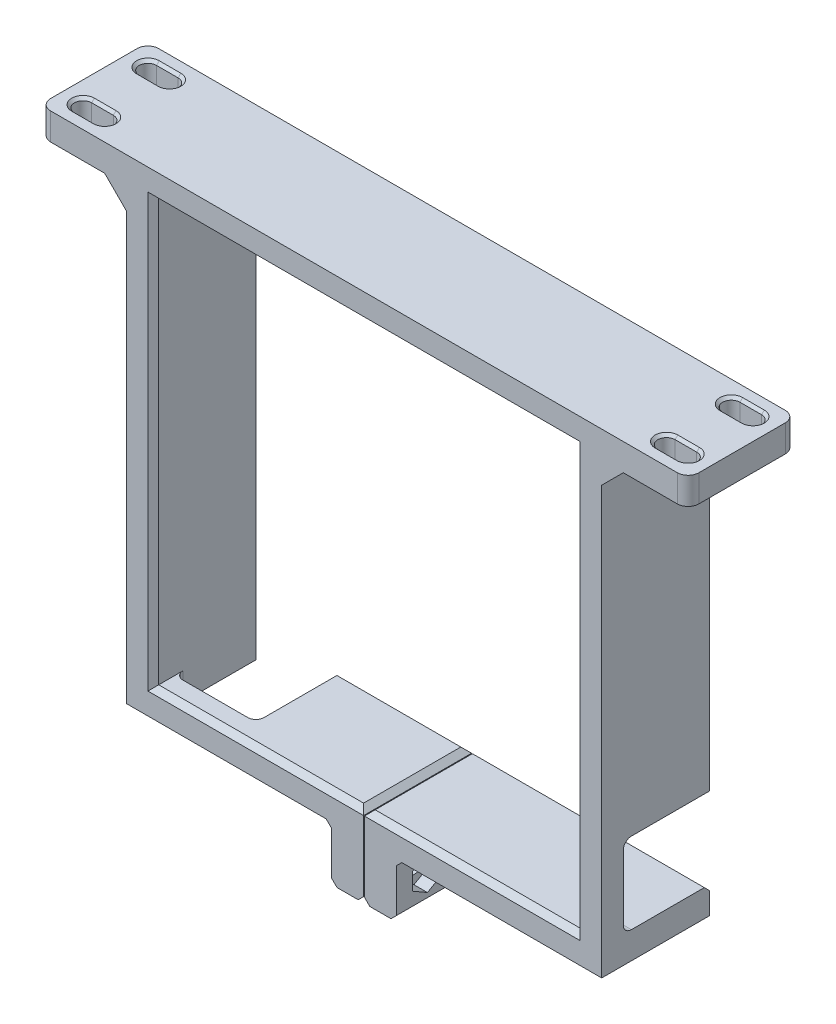
SolidWorks part; units mm, degrees
ref_plane "Front Plane" through (0, 0, 0) normal (0, 0, 1) x (1, 0, 0)
ref_plane "Top Plane" through (0, 0, 0) normal (0, 1, 0) x (1, 0, 0)
ref_plane "Right Plane" through (0, 0, 0) normal (1, 0, 0) x (0, 0, -1)
sketch "Sketch1" plane through (0, 0, 0) normal (0, 0, 1) x (1, 0, 0)
  line L0 (-44.015, -44.015) -> (-44.015, 44.015)
  line L1 (-39.015, -39.015) -> (39.015, -39.015)
  line L2 (-39.015, -39.015) -> (-39.015, 39.015)
  line L3 (-39.015, 39.015) -> (39.015, 39.015)
  line L4 (39.015, -39.015) -> (39.015, 39.015)
  line L5 (-39.015, -39.015) -> (39.015, 39.015) construction
  line L6 (-39.015, 39.015) -> (39.015, -39.015) construction
  line L7 (-44.015, 44.015) -> (44.015, 44.015)
  line L8 (44.015, -44.015) -> (44.015, 44.015)
  line L9 (-44.015, -44.015) -> (44.015, -44.015)
  point P0 (0, 0)
  dimension "D1" = 78.03
  dimension "D2" = 78.03
  dimension "D3" = 5
extrude "Boss-Extrude1" add sketch "Sketch1" along normal blind 20
sketch "Sketch2" plane through (44.015, 0, 0) normal (1, 0, 0) x (0, 0, -1)
  line L0 (-20, -44.015) -> (-20, 44.015) construction
  line L3 (0, -24.015) -> (-16, -24.015)
  line L4 (-16, -39.015) -> (-16, -24.015)
  line L5 (-16, -39.015) -> (0, -39.015)
  line L6 (0, -44.015) -> (0, 44.015) construction
  line L7 (0, -39.015) -> (0, -24.015)
  line L8 (-20, -39.015) -> (0, -39.015) construction
  line L9 (-20, -39.015) -> (0, -39.015) construction
  dimension "D1" = 4
  dimension "D2" = 15
extrude "Cut-Extrude1" cut sketch "Sketch2" against normal blind 20
sketch "Sketch5" plane through (0, 0, 0) normal (0, 0, -1) x (-1, 0, 0)
  line L0 (44.015, -44.015) -> (-44.015, -44.015) construction
  line L1 (-6, -44.015) -> (6, -44.015)
  line L2 (-6, -44.015) -> (-6, -54.015)
  line L3 (-6, -54.015) -> (6, -54.015)
  line L4 (6, -44.015) -> (6, -54.015)
  point P6 (0, -44.015)
  dimension "D1" = 12
  dimension "D2" = 10
extrude "Boss-Extrude2" add sketch "Sketch5" against normal up to surface (20 mm away) up to face at (0, 0, 20)
sketch "Sketch3" plane through (0, 0, 0) normal (0, 0, -1) x (-1, 0, 0)
  line L0 (39.015, -39.015) -> (-44.015, -39.015) construction
  line L1 (-0.075, -39.015) -> (0.075, -39.015)
  line L2 (-0.075, -39.015) -> (-0.075, -54.015)
  line L3 (-0.075, -54.015) -> (0.075, -54.015)
  line L4 (0.075, -39.015) -> (0.075, -54.015)
  line L6 (-6, -54.015) -> (6, -54.015) construction
  point P8 (0, -39.015)
  dimension "D1" = 0.15
extrude "Cut-Extrude2" cut sketch "Sketch3" against normal through all
sketch "Sketch6" plane through (-6, 0, 0) normal (-1, 0, 0) x (0, 0, 1)
  line L0 (0, -54.015) -> (0, -44.015) construction
  line L1 (8.5, -47.4273) -> (5.75, -45.8396)
  line L2 (5.75, -45.8396) -> (3, -47.4273)
  line L3 (3, -47.4273) -> (3, -50.6027)
  line L4 (3, -50.6027) -> (5.75, -52.1904)
  line L5 (5.75, -52.1904) -> (8.5, -50.6027)
  line L6 (8.5, -50.6027) -> (8.5, -47.4273)
  line L8 (17, -47.4273) -> (14.25, -45.8396)
  line L9 (14.25, -45.8396) -> (11.5, -47.4273)
  line L10 (11.5, -47.4273) -> (11.5, -50.6027)
  line L11 (11.5, -50.6027) -> (14.25, -52.1904)
  line L12 (14.25, -52.1904) -> (17, -50.6027)
  line L13 (17, -50.6027) -> (17, -47.4273)
  line L14 (20, -54.015) -> (20, -44.015) construction
  circle A0 centre (5.75, -49.015) radius 2.75 construction
  circle A1 centre (14.25, -49.015) radius 2.75 construction
  point P11 (0, -49.015)
  dimension "D1" = 5.5
  dimension "D2" = 3
  dimension "D3" = 3
extrude "Cut-Extrude3" cut sketch "Sketch6" against normal blind 2.5
sketch "Sketch7" plane through (-6, 0, 0) normal (-1, 0, 0) x (0, 0, 1)
  line L0 (0, -54.015) -> (0, -44.015) construction
  line L1 (20, -54.015) -> (20, -44.015) construction
  circle A0 centre (5.75, -49.015) radius 1.55
  circle A1 centre (14.25, -49.015) radius 1.55
  point P8 (0, -49.015)
  dimension "D3" = 3.1
  dimension "D1" = 5.75
  dimension "D2" = 5.75
extrude "Cut-Extrude4" cut sketch "Sketch7" against normal through all both and the other way through all
sketch "Sketch8" plane through (0, 0, 0) normal (0, 0, -1) x (-1, 0, 0)
  line L0 (-44.015, 39.015) -> (-60.015, 39.015)
  line L1 (-44.015, -24.015) -> (-44.015, 44.015) construction
  line L2 (-60.015, 39.015) -> (-60.015, 44.015)
  line L3 (-60.015, 44.015) -> (-44.015, 44.015)
  line L4 (-39.015, 39.015) -> (39.015, 39.015) construction
  line L5 (-39.015, 39.015) -> (39.015, 39.015) construction
  line L6 (-44.015, 44.015) -> (-44.015, 39.015)
  dimension "D1" = 16
extrude "Boss-Extrude3" add sketch "Sketch8" against normal up to surface (20 mm away) up to face at (0, -23.8825, 20)
sketch "Sketch9" plane through (0, 44.015, 0) normal (0, 1, 0) x (1, 0, 0)
  line L0 (44.015, -20) -> (44.015, 0) construction
  line L1 (44.015, -20) -> (44.015, 0) construction
  line L2 (60.015, -20) -> (60.015, 0) construction
  line L7 (52.015, -16) -> (56.015, -16) construction
  line L8 (52.015, -14.4) -> (56.015, -14.4)
  line L9 (52.015, -17.6) -> (56.015, -17.6)
  line L10 (52.015, -4) -> (56.015, -4) construction
  line L11 (52.015, -2.4) -> (56.015, -2.4)
  line L12 (52.015, -5.6) -> (56.015, -5.6)
  line L13 (44.015, -20) -> (60.015, -20) construction
  line L15 (60.015, 0) -> (-44.015, 0) construction
  arc A0 (52.015, -14.4) -> (52.015, -17.6) centre (52.015, -16) ccw
  arc A1 (56.015, -17.6) -> (56.015, -14.4) centre (56.015, -16) ccw
  arc A2 (52.015, -2.4) -> (52.015, -5.6) centre (52.015, -4) ccw
  arc A3 (56.015, -5.6) -> (56.015, -2.4) centre (56.015, -4) ccw
  point P12 (54.015, -16)
  point P17 (54.015, -4)
  dimension "D2" = 1.6
  dimension "D3" = 4
  dimension "D4" = 4
  dimension "D5" = 4
  dimension "D6" = 4
extrude "Cut-Extrude5" cut sketch "Sketch9" against normal through all
fillet "Fillet8" radius 2 2 edges at (60.015, 41.515, 0) (60.015, 41.515, 20)
fillet "Fillet2" [suppressed] radius 1
mirror "Mirror9" about plane through (0, 0, 0) normal (1, 0, 0) of "Fillet8", "Cut-Extrude5", "Boss-Extrude3", "Cut-Extrude4", "Cut-Extrude3"
chamfer "Chamfer1" distance 4 angle 45 2 edges at (44.015, 39.015, 10) (-44.015, 39.015, 10)
sketch "Sketch10" plane through (0, -44.015, 0) normal (0, -1, 0) x (1, 0, 0)
  line L0 (-39.015, 20) -> (-39.015, 0) construction
  line L1 (-39.015, 20) -> (-39.015, 0) construction
  line L2 (-44.015, 20) -> (-6, 20) construction
  line L3 (-39.015, 0) -> (-24.015, 0)
  line L4 (-39.015, 0) -> (-39.015, 16)
  line L5 (-39.015, 16) -> (-24.015, 16)
  line L6 (-24.015, 0) -> (-24.015, 16)
  dimension "D1" = 4
  dimension "D2" = 15
extrude "Cut-Extrude6" cut sketch "Sketch10" against normal blind 15
fillet "Fillet7" radius 1.5 3 edges at (-39.015, -41.515, 16) (-24.015, -41.515, 16) (41.515, -24.015, 16)
chamfer "Chamfer2" distance 1 angle 45 18 edges at (0, 39.015, 0) (-39.015, -2.5, 0) (39.015, 0, 20) (0, 39.015, 20) (-39.015, 0, 20) (-19.545, -39.015, 20) (39.015, 7.5, 0) (-12.045, -39.015, 0) (-6, -54.015, 10) (-6, -44.015, 10) (6, -44.015, 10) (6, -54.015, 10) (22.045, -39.015, 0) (19.545, -39.015, 20) (0.075, -54.015, 10) (0.075, -39.015, 10) (-0.075, -39.015, 10) (-0.075, -54.015, 10)
chamfer "Chamfer3" distance 0.5 angle 45 32 edges at (-54.015, 39.015, 14.4) (-54.015, 44.015, 14.4) (-50.415, 39.015, 16) (-50.415, 44.015, 16) (-57.615, 39.015, 16) (-57.615, 44.015, 16) (-54.015, 39.015, 17.6) (-54.015, 44.015, 17.6) (-57.615, 39.015, 4) (-54.015, 39.015, 2.4) (-54.015, 39.015, 5.6) (-50.415, 39.015, 4) (-54.015, 44.015, 2.4) (-50.415, 44.015, 4) (-57.615, 44.015, 4) (-54.015, 44.015, 5.6) (54.015, 44.015, 14.4) (50.415, 44.015, 16) (57.615, 44.015, 16) (54.015, 44.015, 17.6) (54.015, 44.015, 2.4) (50.415, 44.015, 4) (57.615, 44.015, 4) (54.015, 44.015, 5.6) (54.015, 39.015, 17.6) (50.415, 39.015, 16) (57.615, 39.015, 16) (54.015, 39.015, 14.4) (54.015, 39.015, 5.6) (50.415, 39.015, 4) (57.615, 39.015, 4) (54.015, 39.015, 2.4)
